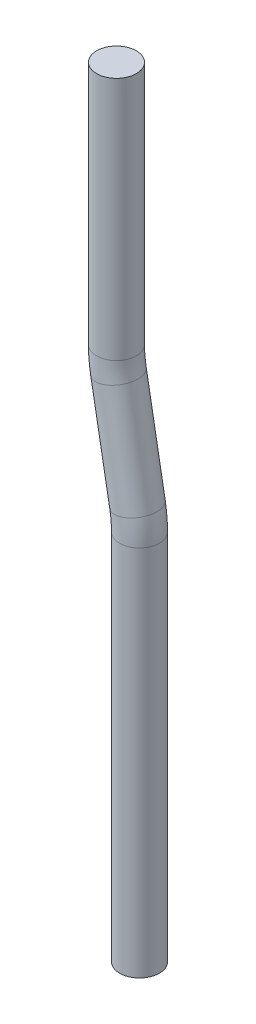
SolidWorks part; units mm, degrees
ref_plane "Front Plane" through (0, 0, 0) normal (0, 0, 1) x (1, 0, 0)
ref_plane "Top Plane" through (0, 0, 0) normal (0, 1, 0) x (1, 0, 0)
ref_plane "Right Plane" through (0, 0, 0) normal (1, 0, 0) x (0, 0, -1)
sketch "Sketch1" plane through (0, 0, 0) normal (0, 1, 0) x (1, 0, 0)
  circle A0 centre (0, 0) radius 3.937
  dimension "D1" = 7.874
sketch "Sketch2" plane through (0, 0, 0) normal (0, 0, 1) x (1, 0, 0)
  line L0 (0, 0) -> (0, -48.5322)
  line L1 (0.4017, -53.0319) -> (4.1703, -73.9681)
  line L2 (4.572, -78.4678) -> (4.572, -152.4)
  arc A0 (4.572, -78.4678) -> (4.1703, -73.9681) centre (-20.828, -78.4678) ccw
  arc A1 (0, -48.5322) -> (0.4017, -53.0319) centre (25.4, -48.5322) ccw
  point P5 (0, 0)
  point P6 (0, 0)
  point P9 (4.572, -76.2)
  point P12 (0, -50.8)
  dimension "D5" = 25.4
  dimension "D1" = 4.572
  dimension "D2" = 50.8
  dimension "D3" = 152.4
  dimension "D4" = 76.2
sweep "Sweep1" add profiles "Sketch1" path "Sketch2"
